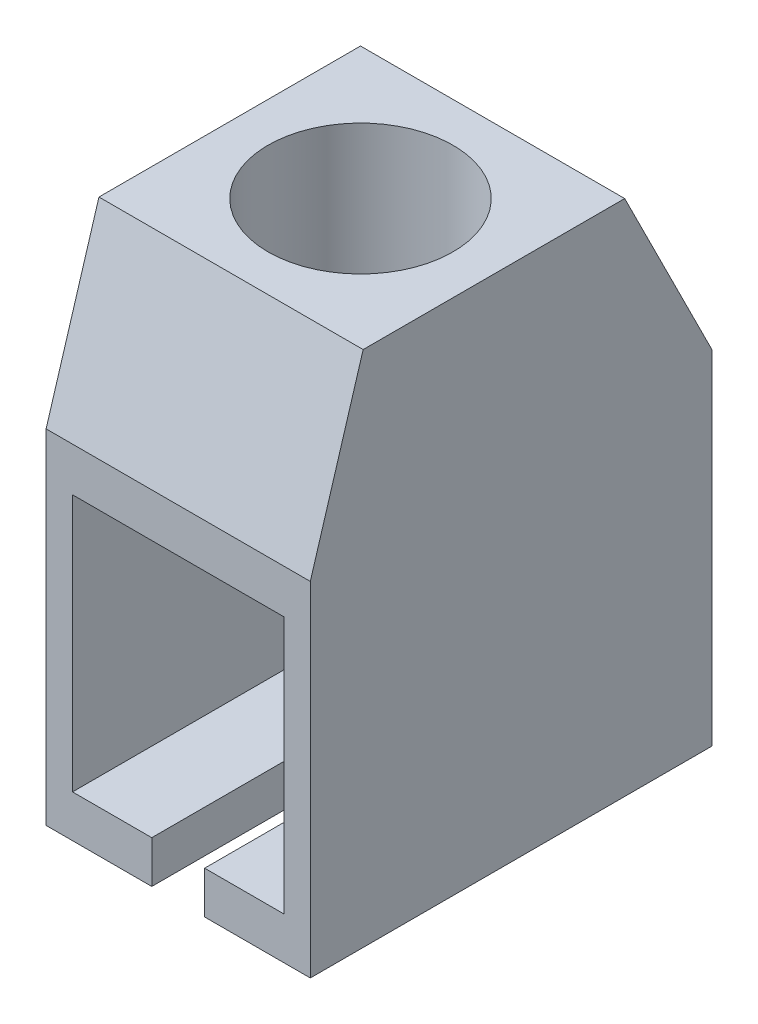
SolidWorks part; units mm, degrees
ref_plane "Спереди" through (0, 0, 0) normal (0, 0, 1) x (1, 0, 0)
ref_plane "Сверху" through (0, 0, 0) normal (0, 1, 0) x (1, 0, 0)
ref_plane "Справа" through (0, 0, 0) normal (1, 0, 0) x (0, 0, -1)
sketch "Эскиз1" plane through (0, 0, 0) normal (0, 1, 0) x (1, 0, 0)
  line L1 (-2.5, 3.8) -> (2.5, 3.8)
  line L2 (-2.5, 3.8) -> (-2.5, -3.8)
  line L3 (-2.5, -3.8) -> (2.5, -3.8)
  line L4 (2.5, 3.8) -> (2.5, -3.8)
  dimension "D1" = 5
  dimension "D2" = 7.6
  dimension "D3" = 3.8
  dimension "D4" = 2.5
extrude "Бобышка-Вытянуть1" add sketch "Эскиз1" along normal blind 6.5
sketch "Эскиз2" plane through (0, 0, 0) normal (0, -1, 0) x (1, 0, 0)
  line L0 (-2.5, 3.8) -> (2.5, 3.8) construction
  line L1 (0.5, 3.8) -> (-0.5, 3.8)
  line L2 (0.5, 3.8) -> (0.5, 0.05)
  line L3 (0.5, 0.05) -> (-0.5, 0.05)
  line L4 (-0.5, 3.8) -> (-0.5, 0.05)
  line L5 (-2.5, -3.8) -> (-2.5, 3.8) construction
  dimension "D1" = 1
  dimension "D2" = 2
  dimension "D3" = 3.75
extrude "Вырез-Вытянуть1" cut sketch "Эскиз2" against normal blind 2
sketch "Эскиз3" plane through (0, 0, 3.8) normal (0, 0, 1) x (1, 0, 0)
  line L0 (-2.5, 0) -> (-0.5, 0) construction
  line L1 (-2, 5.67) -> (2, 5.67)
  line L2 (-2, 5.67) -> (-2, 0.8)
  line L3 (-2, 0.8) -> (2, 0.8)
  line L4 (2, 5.67) -> (2, 0.8)
  line L5 (2.5, 6.5) -> (2.5, 0) construction
  dimension "D1" = 4
  dimension "D2" = 4.87
  dimension "D3" = 0.8
  dimension "D4" = 0.5
extrude "Вырез-Вытянуть2" cut sketch "Эскиз3" against normal blind 6.8
sketch "Эскиз4" plane through (0, 6.5, 0) normal (0, 1, 0) x (1, 0, 0)
  line L1 (-2.5, 3.8) -> (2.5, 3.8)
  line L2 (-2.5, 3.8) -> (-2.5, -3.8)
  line L3 (-2.5, -3.8) -> (2.5, -3.8)
  line L4 (2.5, 3.8) -> (2.5, -3.8)
extrude "Бобышка-Вытянуть2" add sketch "Эскиз4" along normal blind 3.3
chamfer "Фаска1" distance 3.3 distance2 1 1 edges at (0, 9.8, 3.8)
chamfer "Фаска2" distance 3.3 distance2 1.65 1 edges at (0, 9.8, -3.8)
sketch "Эскиз5" plane through (0, 5.67, 0) normal (0, -1, 0) x (1, 0, 0)
  line L0 (-2, -3) -> (-2, 3.8) construction
  line L1 (2, -3) -> (-2, -3) construction
  circle A0 centre (0, -2.6) radius 0.4
  dimension "D2" = 0.8
  dimension "D1" = 2
extrude "Вырез-Вытянуть3" cut sketch "Эскиз5" against normal blind 5
sketch "Эскиз6" plane through (0, 9.8, 0) normal (0, 1, 0) x (1, 0, 0)
  line L2 (2.5, 2.15) -> (-2.5, 2.15) construction
  circle A0 centre (0, -0.35) radius 1.75
  dimension "D1" = 3.5
  dimension "D2" = 2.5
extrude "Вырез-Вытянуть4" cut sketch "Эскиз6" along direction (0, 1, 0) on the side against the normal up to surface (4.13 mm away)
